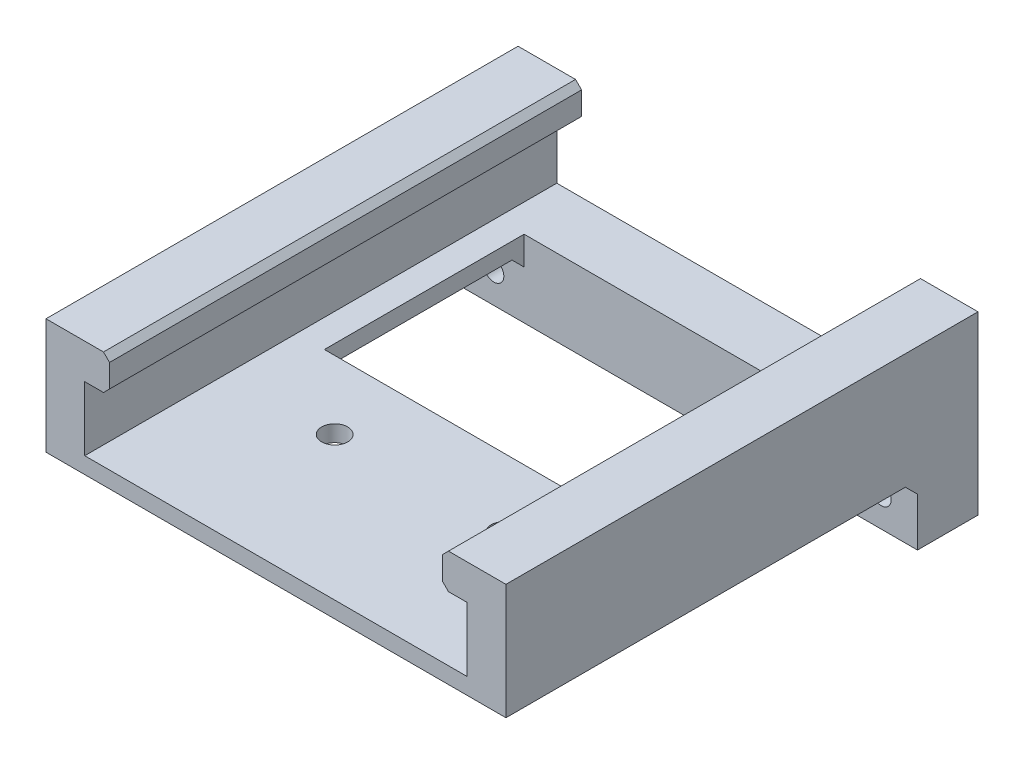
SolidWorks part; units mm, degrees
material "1060 合金"
ref_plane "前视基准面" through (0, 0, 0) normal (0, 0, 1) x (1, 0, 0)
ref_plane "上视基准面" through (0, 0, 0) normal (0, 1, 0) x (1, 0, 0)
ref_plane "右视基准面" through (0, 0, 0) normal (1, 0, 0) x (0, 0, -1)
sketch "草图1" plane through (0, 0, 0) normal (0, 0, 1) x (1, 0, 0)
  line L0 (-27.5, 19.1) -> (-38, 19.1)
  line L1 (-38, 19.1) -> (-38, 0)
  line L2 (-27.5, 19.1) -> (-27.5, 13.3)
  line L3 (-27.5, 13.3) -> (-31.6, 13.3)
  line L4 (-31.6, 13.3) -> (-31.6, 2.7)
  line L5 (0, 0) -> (0, 43.3652) construction
  line L6 (31.6, 13.3) -> (31.6, 2.7)
  line L7 (27.5, 13.3) -> (31.6, 13.3)
  line L8 (27.5, 19.1) -> (27.5, 13.3)
  line L9 (38, 19.1) -> (38, 0)
  line L10 (27.5, 19.1) -> (38, 19.1)
  line L11 (-31.6, 2.7) -> (31.6, 2.7)
  line L12 (-38, 0) -> (38, 0)
  dimension "D1" = 63.2
  dimension "D2" = 55
  dimension "D3" = 5.8
  dimension "D4" = 10.6
  dimension "D5" = 76
  dimension "D6" = 19.1
extrude "凸台-拉伸1" add sketch "草图1" along normal mid plane 78
hole_wizard "M3 螺纹孔1" [suppressed] positions "草图3" profile "草图2" tap size "M3" standard "GB"
sketch "草图3" plane through (0, 0, 0) normal (0, -1, 0) x (-1, 0, 0)
  line L0 (0, 0) -> (0, 40.318) construction
  line L2 (38, -39) -> (-38, -39) construction
  line L3 (38, 39) -> (-38, 39) construction
  point P0 (34.8, 33)
  point P2 (34.8, -33)
  point P12 (-34.8, -33)
  point P13 (-34.8, 33)
  dimension "D1" = 69.6
  dimension "D2" = 6
  dimension "D3" = 6
sketch "草图2" plane through (-34.8, 0, -33) normal (1, 0, 0) x (0, 0, -1)
  line L0 (0, 0) -> (0, 14.7511)
  line L1 (0, 14.7511) -> (1.25, 14)
  line L2 (1.25, 14) -> (1.25, 13.5)
  line L3 (1.25, 13.5) -> (1.5, 13.5)
  line L4 (1.5, 13.5) -> (1.5, 0)
  line L5 (1.5, 0) -> (0, 0)
  line L10 (0, 14.7511) -> (-1.25, 14) construction
  line L11 (0, -6.35) -> (0, 107.95) construction
  dimension "螺纹孔钻头直径" = 2.5
  dimension "螺纹孔钻头深度" = 14
  dimension "螺纹主直径" = 3
  dimension "螺纹深度" = 13.5
  dimension "导头角度" = 118
hole_wizard "M4 间隙孔1" positions "草图5" profile "草图4" hole size "M4" standard "GB" end condition up to next
sketch "草图5" plane through (0, 0, 0) normal (0, -1, 0) x (-1, 0, 0)
  line L1 (0, 0) -> (0, 26.3665) construction
  line L3 (38, 39) -> (-38, 39) construction
  point P0 (-14, -15.3)
  point P2 (14, -15.3)
  dimension "D1" = 28
  dimension "D2" = 54.3
sketch "草图4" plane through (14, 0, 15.3) normal (1, 0, 0) x (0, 0, -1)
  line L0 (0, 0) -> (0, 2.7)
  line L1 (0, 2.7) -> (2.15, 2.7)
  line L2 (2.15, 2.7) -> (2.15, 0)
  line L5 (2.15, 0) -> (0, 0)
  line L11 (0, -6.35) -> (0, 107.95) construction
  dimension "通孔孔直径" = 4.3
  dimension "通孔孔深度" = 2.7
sketch "草图6" plane through (0, 2.7, 0) normal (0, 1, 0) x (1, 0, 0)
  line L1 (-27.5, 39) -> (27.5, 39)
  line L2 (-27.5, 39) -> (-27.5, 32.7)
  line L3 (-27.5, 32.7) -> (27.5, 32.7)
  line L4 (27.5, 39) -> (27.5, 32.7)
  line L5 (-27.5, 39) -> (27.5, 32.7) construction
  line L6 (-27.5, 32.7) -> (27.5, 39) construction
  line L7 (27.5, -39) -> (27.5, 39) construction
  line L8 (31.6, 39) -> (-31.6, 39) construction
  point P0 (0, 35.85)
  dimension "D1" = 0
  dimension "D2" = 6.3
extrude "切除-拉伸1" [suppressed] cut sketch "草图6" against normal up to next
chamfer "倒角1" distance 1 angle 45 4 edges at (27.5, 13.3, 0) (27.5, 19.1, 0) (-27.5, 19.1, 0) (-27.5, 13.3, 0)
sketch "草图8" plane through (0, 0, 0) normal (0, -1, 0) x (1, 0, 0)
  line L0 (38, 39) -> (38, -39) construction
  line L1 (-38, -29) -> (38, -29)
  line L2 (-38, -29) -> (-38, -39)
  line L3 (-38, -39) -> (38, -39)
  line L4 (38, -29) -> (38, -39)
  line L5 (-38, -29) -> (38, -39) construction
  line L6 (-38, -39) -> (38, -29) construction
  line L8 (-38, -39) -> (38, -39) construction
  point P0 (0, -34)
  dimension "D1" = 10
extrude "凸台-拉伸2" add sketch "草图8" along normal blind 10
sketch "草图9" plane through (0, 0, 0) normal (0, -1, 0) x (1, 0, 0)
  line L1 (-27, -29) -> (27, -29)
  line L2 (-27, -29) -> (-27, 4)
  line L3 (-27, 4) -> (27, 4)
  line L4 (27, -29) -> (27, 4)
  line L5 (-27, -29) -> (27, 4) construction
  line L6 (-27, 4) -> (27, -29) construction
  line L7 (-38, -39) -> (38, -39) construction
  line L8 (38, -29) -> (-38, -29) construction
  point P0 (0, -12.5)
  dimension "D1" = 43
  dimension "D3" = 54
extrude "切除-拉伸2" cut sketch "草图9" against normal up to next
chamfer "倒角2" distance 2 angle 45 2 edges
hole_wizard "M4 螺纹孔1" positions "草图11" profile "草图10" tap size "M4" standard "GB" end condition up to next
sketch "草图11" plane through (0, 0, -39) normal (0, 0, -1) x (-1, 0, 0)
  line L0 (0, 0) -> (0, 26.3255) construction
  line L2 (-38, -10) -> (-38, 19.1) construction
  line L3 (38, -10) -> (-38, -10) construction
  point P0 (32, -5)
  point P2 (-32, -5)
  dimension "D1" = 6
  dimension "D2" = 5
sketch "草图10" plane through (-32, -5, -39) normal (1, 0, 0) x (0, 1, 0)
  line L0 (0, 0) -> (0, 10)
  line L1 (0, 10) -> (1.65, 10)
  line L2 (1.65, 10) -> (1.65, 0)
  line L5 (1.65, 0) -> (0, 0)
  line L11 (0, -6.35) -> (0, 107.95) construction
  dimension "通孔螺纹孔钻头直径" = 3.3
  dimension "通孔螺纹孔钻头深度" = 10
cosmetic thread "孔螺蚊线1" parameters "D2"=4
cosmetic thread "孔螺蚊线2" parameters "D2"=4
